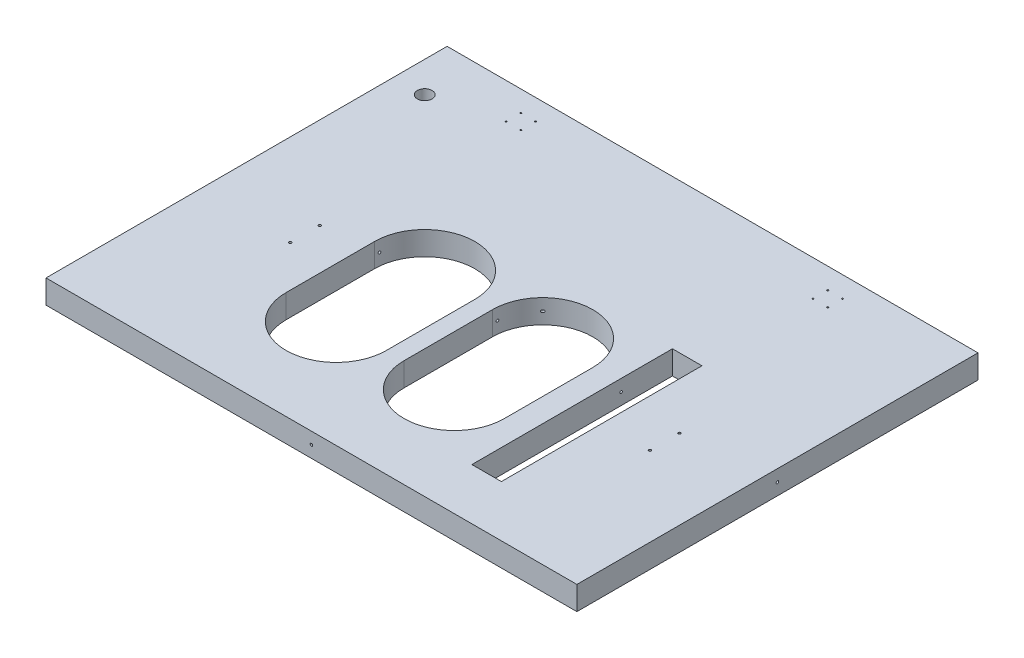
SolidWorks part; units mm, degrees
material "1.4511 (X3CrNb17)"
ref_plane "前视基准面" through (0, 0, 0) normal (0, 0, 1) x (1, 0, 0)
ref_plane "上视基准面" through (0, 0, 0) normal (0, 1, 0) x (1, 0, 0)
ref_plane "右视基准面" through (0, 0, 0) normal (1, 0, 0) x (0, 0, -1)
sketch "草图1" plane through (0, 0, 0) normal (0, 1, 0) x (1, 0, 0)
  line L1 (-450, 340) -> (450, 340)
  line L2 (-450, 340) -> (-450, -340)
  line L3 (-450, -340) -> (450, -340)
  line L4 (450, 340) -> (450, -340)
  line L5 (-450, 340) -> (450, -340) construction
  line L6 (-450, -340) -> (450, 340) construction
  point P0 (0, 0)
  dimension "D1" = 900
  dimension "D2" = 680
extrude "凸台-拉伸1" add sketch "草图1" along normal blind 40
sketch "草图2" plane through (0, 40, 0) normal (0, 1, 0) x (1, 0, 0)
  line L2 (-25, -8) -> (-25, -158)
  line L4 (145, -8) -> (145, -158)
  line L6 (-225, -8) -> (-225, -158)
  line L7 (185, 87) -> (235, 87)
  line L8 (185, 87) -> (185, -253)
  line L9 (185, -253) -> (235, -253)
  line L10 (235, 87) -> (235, -253)
  line L11 (-55, -8) -> (-55, -158)
  arc A0 (-25, -158) -> (145, -158) centre (60, -158) ccw
  arc A1 (145, -8) -> (-25, -8) centre (60, -8) ccw
  arc A4 (-55, -8) -> (-225, -8) centre (-140, -8) ccw
  arc A5 (-225, -158) -> (-55, -158) centre (-140, -158) ccw
  point P0 (50, 0)
  point P14 (200, 0)
  dimension "D1" = 170
  dimension "D2" = 150
  dimension "D3" = 50
  dimension "D4" = 200
  dimension "D5" = 50
  dimension "D6" = 340
extrude "切除-拉伸1" cut sketch "草图2" against normal through all
sketch "草图3" plane through (0, 0, 340) normal (0, 0, 1) x (1, 0, 0)
  line L0 (-450, 40) -> (-450, 0) construction
  point P0 (0, 20)
  dimension "D1" = 450
hole_wizard "M5 螺纹孔1" positions "草图4" profile "草图5" tap size "M5" standard "GB" end condition through all
sketch "草图4" plane through (0, 0, 340) normal (0, 0, 1) x (1, 0, 0)
  point P0 (0, 20)
sketch "草图5" plane through (0, 20, 340) normal (1, 0, 0) x (0, -1, 0)
  line L0 (0, 0) -> (0, 680)
  line L1 (0, 680) -> (2.1, 680)
  line L2 (2.1, 680) -> (2.1, 0)
  line L5 (2.1, 0) -> (0, 0)
  line L11 (0, -6.35) -> (0, 107.95) construction
  dimension "通孔螺纹孔钻头直径" = 4.2
  dimension "通孔螺纹孔钻头深度" = 680
cosmetic thread "孔螺蚊线1" parameters "D2"=5
sketch "草图6" plane through (-450, 0, 0) normal (-1, 0, 0) x (0, 0, 1)
  line L0 (-340, 40) -> (-340, 0) construction
  point P0 (0, 20)
  dimension "D1" = 340
hole_wizard "M5 螺纹孔2" positions "草图7" profile "草图8" tap size "M5" standard "GB" end condition through all
sketch "草图7" plane through (-450, 0, 0) normal (-1, 0, 0) x (0, 0, 1)
  point P0 (0, 20)
sketch "草图8" plane through (-450, 20, 0) normal (0, 1, 0) x (0, 0, 1)
  line L0 (0, 0) -> (0, 900)
  line L1 (0, 900) -> (2.1, 900)
  line L2 (2.1, 900) -> (2.1, 0)
  line L5 (2.1, 0) -> (0, 0)
  line L11 (0, -6.35) -> (0, 107.95) construction
  dimension "通孔螺纹孔钻头直径" = 4.2
  dimension "通孔螺纹孔钻头深度" = 900
cosmetic thread "孔螺蚊线2" parameters "D2"=5
sketch "草图9" plane through (0, 40, 0) normal (0, 1, 0) x (1, 0, 0)
  line L0 (450, 340) -> (-450, 340) construction
  line L1 (-450, 340) -> (-450, -340) construction
  circle A0 centre (-398, 250) radius 12.5
  dimension "D1" = 25
  dimension "D2" = 90
  dimension "D3" = 52
extrude "切除-拉伸2" cut sketch "草图9" against normal through all
sketch "草图10" plane through (0, 40, 0) normal (0, 1, 0) x (1, 0, 0)
  line L0 (-450, 340) -> (-450, -340) construction
  line L1 (-450, -340) -> (450, -340) construction
  point P0 (-295, -81.1)
  point P5 (-295, -31.1)
  point P6 (315, -81.1)
  point P7 (315, -31.1)
  dimension "D1" = 155
  dimension "D2" = 258.9
  dimension "D4" = 610
  dimension "D3" = 2
  dimension "D5" = 2
hole_wizard "M5 螺纹孔3" positions "草图11" profile "草图13" tap size "M5" standard "GB"
sketch "草图11" plane through (0, 40, 0) normal (0, 1, 0) x (1, 0, 0)
  point P0 (-295, -31.1)
  point P3 (-295, -81.1)
  point P8 (315, -31.1)
  point P11 (315, -81.1)
sketch "草图13" plane through (-295, 40, 31.1) normal (1, 0, 0) x (0, 0, 1)
  line L0 (0, 0) -> (0, 6.4618)
  line L1 (0, 6.4618) -> (2.1, 5.2)
  line L2 (2.1, 5.2) -> (2.1, 0)
  line L5 (2.1, 0) -> (0, 0)
  line L10 (0, 6.4618) -> (-2.1, 5.2) construction
  line L11 (0, -6.35) -> (0, 107.95) construction
  dimension "螺纹孔钻头直径" = 4.2
  dimension "螺纹孔钻头深度" = 5.2
  dimension "导头角度" = 118
cosmetic thread "孔螺蚊线3" parameters "D1"=8.2, "D2"=5
cosmetic thread "孔螺蚊线4" parameters "D1"=8.2, "D2"=5
cosmetic thread "孔螺蚊线5" parameters "D1"=8.2, "D2"=5
cosmetic thread "孔螺蚊线6" parameters "D1"=8.2, "D2"=5
sketch "草图14" plane through (0, 40, 0) normal (0, 1, 0) x (1, 0, 0)
  line L0 (-277, 292) -> (243.3, 292) construction
  line L1 (450, 340) -> (-450, 340) construction
  line L2 (-450, 340) -> (-450, -340) construction
  line L4 (-289.5, 304.5) -> (-264.5, 304.5) construction
  line L5 (-289.5, 304.5) -> (-289.5, 279.5) construction
  line L6 (-289.5, 279.5) -> (-264.5, 279.5) construction
  line L7 (-264.5, 304.5) -> (-264.5, 279.5) construction
  line L8 (-289.5, 304.5) -> (-264.5, 279.5) construction
  line L9 (-289.5, 279.5) -> (-264.5, 304.5) construction
  line L10 (230.8, 304.5) -> (255.8, 304.5) construction
  line L11 (230.8, 304.5) -> (230.8, 279.5) construction
  line L12 (230.8, 279.5) -> (255.8, 279.5) construction
  line L13 (255.8, 304.5) -> (255.8, 279.5) construction
  line L14 (230.8, 304.5) -> (255.8, 279.5) construction
  line L15 (230.8, 279.5) -> (255.8, 304.5) construction
  dimension "D1" = 520.3
  dimension "D2" = 48
  dimension "D3" = 173
  dimension "D4" = 25
  dimension "D5" = 25
  dimension "D6" = 25
  dimension "D7" = 25
hole_wizard "M3 螺纹孔1" positions "草图15" profile "草图17" tap size "M3" standard "GB"
sketch "草图15" plane through (0, 40, 0) normal (0, 1, 0) x (1, 0, 0)
  point P0 (-289.5, 304.5)
  point P3 (-264.5, 304.5)
  point P6 (-264.5, 279.5)
  point P9 (-289.5, 279.5)
  point P12 (255.8, 304.5)
  point P15 (255.8, 279.5)
  point P18 (230.8, 279.5)
  point P21 (230.8, 304.5)
sketch "草图17" plane through (-289.5, 40, -304.5) normal (1, 0, 0) x (0, 0, 1)
  line L0 (0, 0) -> (0, 9.2511)
  line L1 (0, 9.2511) -> (1.25, 8.5)
  line L2 (1.25, 8.5) -> (1.25, 0)
  line L5 (1.25, 0) -> (0, 0)
  line L10 (0, 9.2511) -> (-1.25, 8.5) construction
  line L11 (0, -6.35) -> (0, 107.95) construction
  dimension "螺纹孔钻头直径" = 2.5
  dimension "螺纹孔钻头深度" = 8.5
  dimension "导头角度" = 118
cosmetic thread "孔螺蚊线7" parameters "D1"=6, "D2"=3
cosmetic thread "孔螺蚊线8" parameters "D1"=6, "D2"=3
cosmetic thread "孔螺蚊线9" parameters "D1"=6, "D2"=3
cosmetic thread "孔螺蚊线10" parameters "D1"=6, "D2"=3
cosmetic thread "孔螺蚊线11" parameters "D1"=6, "D2"=3
cosmetic thread "孔螺蚊线12" parameters "D1"=6, "D2"=3
cosmetic thread "孔螺蚊线13" parameters "D1"=6, "D2"=3
cosmetic thread "孔螺蚊线14" parameters "D1"=6, "D2"=3
